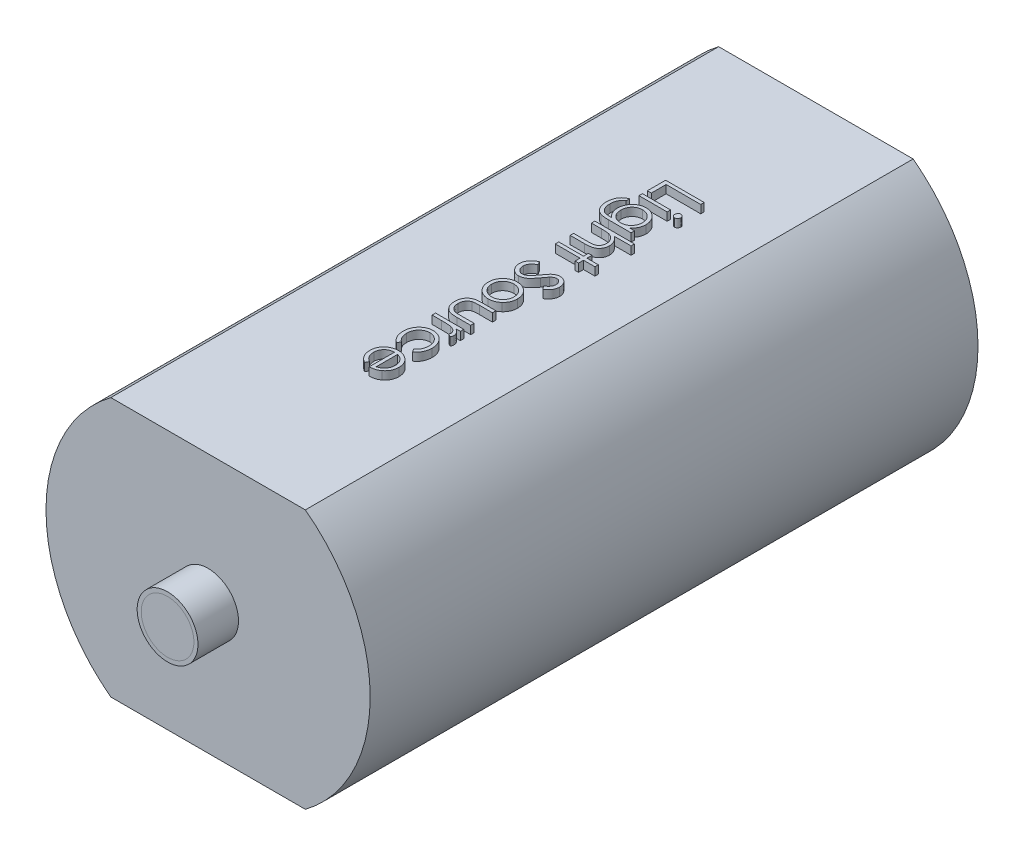
SolidWorks part; units mm, degrees
ref_plane "Front Plane" through (0, 0, 0) normal (0, 0, 1) x (1, 0, 0)
ref_plane "Top Plane" through (0, 0, 0) normal (0, 1, 0) x (1, 0, 0)
ref_plane "Right Plane" through (0, 0, 0) normal (1, 0, 0) x (0, 0, -1)
sketch "Sketch2" plane through (0, 0, 0) normal (0, 0, 1) x (1, 0, 0)
  line L0 (-109.1064, 0) -> (109.1064, 0) construction
  line L1 (0, -64.8192) -> (0, 64.8192) construction
  line L2 (-24, 32) -> (24, 32)
  line L3 (-24, -32) -> (24, -32)
  line L4 (-22.8035, -28.5) -> (22.8035, -28.5)
  line L5 (-22.8035, 28.5) -> (22.8035, 28.5)
  arc A0 (-24, 32) -> (-24, -32) centre (0, 0) ccw
  arc A1 (24, -32) -> (24, 32) centre (0, 0) ccw
  arc A2 (-22.8035, 28.5) -> (-22.8035, -28.5) centre (0, 0) ccw
  arc A3 (22.8035, -28.5) -> (22.8035, 28.5) centre (0, 0) ccw
  point P6 (0, 0)
  point P9 (0, 0)
  point P12 (0, 32)
  dimension "D1" = 80
  dimension "D2" = 32
  dimension "D3" = 3.5
extrude "Boss-Extrude1" add sketch "Sketch2" along normal blind 150
sketch "Sketch3" plane through (0, 0, 0) normal (0, 0, -1) x (-1, 0, 0)
  line L0 (-24, 32) -> (24, 32)
  line L1 (24, -32) -> (-24, -32)
  arc A0 (-24, 32) -> (-24, -32) centre (0, 0) ccw
  arc A1 (24, -32) -> (24, 32) centre (0, 0) ccw
extrude "Boss-Extrude2" add sketch "Sketch3" against normal blind 2
sketch "Sketch4" plane through (0, 0, 150) normal (0, 0, 1) x (1, 0, 0)
  line L0 (-24, 32) -> (24, 32)
  line L1 (24, -32) -> (-24, -32)
  arc A0 (-24, 32) -> (-24, -32) centre (0, 0) ccw
  arc A1 (24, -32) -> (24, 32) centre (0, 0) ccw
extrude "Boss-Extrude3" add sketch "Sketch4" against normal blind 2
sketch "Sketch5" plane through (0, 0, 150) normal (0, 0, 1) x (1, 0, 0)
  circle A0 centre (0, 0) radius 5
  dimension "D1" = 10
extrude "Cut-Extrude1" cut sketch "Sketch5" against normal blind 5
sketch "Sketch6" plane through (0, 32, 0) normal (0, 1, 0) x (1, 0, 0)
  line L0 (0, 0) -> (0, -150) construction
  line L1 (24, -150) -> (-24, -150) construction
  text T0 "Light Source" font "Century Gothic" height in points 36
extrude "Boss-Extrude4" add sketch "Sketch6" along normal blind 2
sketch "Sketch7" plane through (0, 0, 150) normal (0, 0, 1) x (1, 0, 0)
  circle A0 centre (0, 0) radius 5
  circle A1 centre (0, 0) radius 6.5
  dimension "D1" = 10
  dimension "D2" = 13
extrude "Boss-Extrude5" add sketch "Sketch7" along normal blind 8
sketch "Sketch8" plane through (0, 0, 150) normal (0, 0, 1) x (1, 0, 0)
  circle A0 centre (0, 0) radius 6.5
  circle A1 centre (0, 0) radius 7.5
  dimension "D1" = 13
  dimension "D2" = 15
extrude "Boss-Extrude6" add sketch "Sketch8" along normal blind 10
sketch "Sketch9" plane through (0, 0, 160) normal (0, 0, 1) x (1, 0, 0)
  circle A1 centre (0, 0) radius 6.5
  dimension "D2" = 13
extrude "Boss-Extrude8" add sketch "Sketch9" against normal blind 2 separate body
